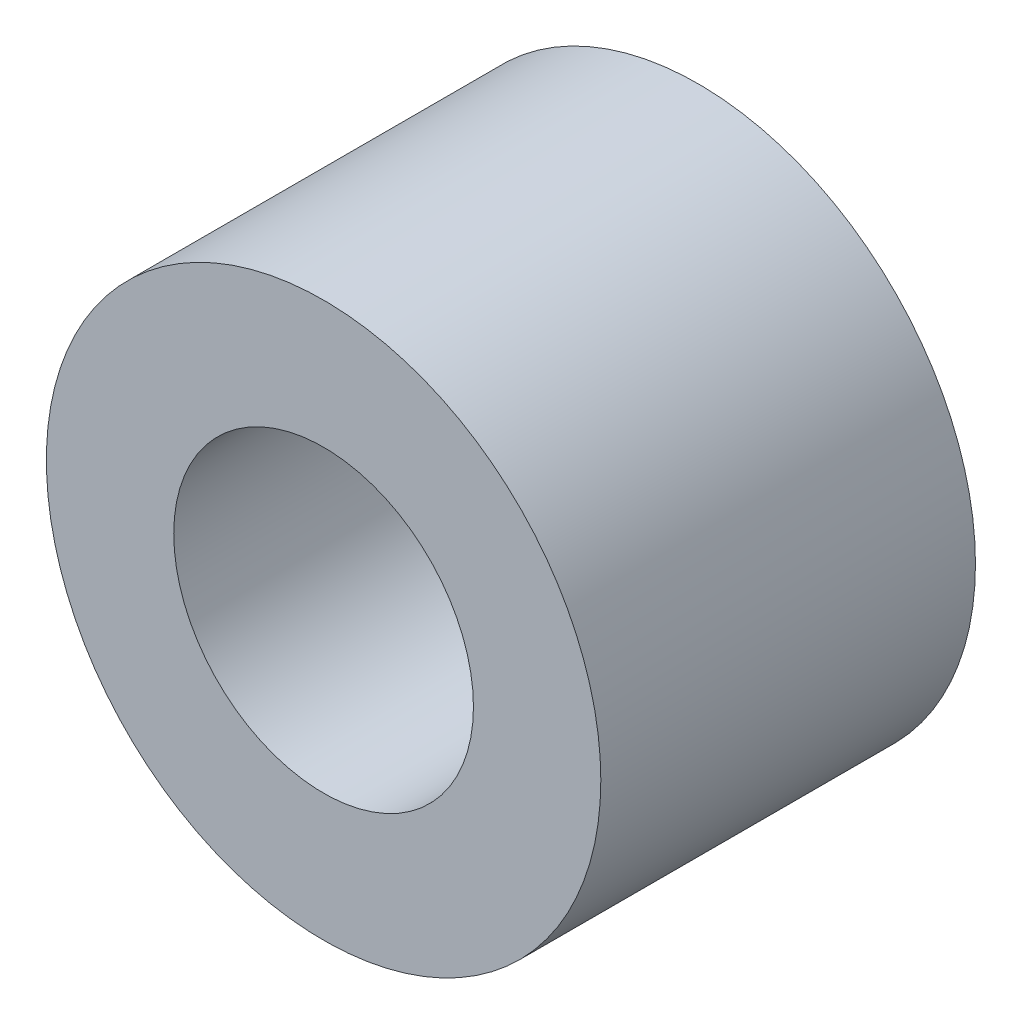
SolidWorks part; units mm, degrees
ref_plane "前视基准面" through (0, 0, 0) normal (0, 0, 1) x (1, 0, 0)
ref_plane "上视基准面" through (0, 0, 0) normal (0, 1, 0) x (1, 0, 0)
ref_plane "右视基准面" through (0, 0, 0) normal (1, 0, 0) x (0, 0, -1)
other "Configuration Table"
sketch "草图1" plane through (0, 0, 0) normal (0, 0, 1) x (1, 0, 0)
  circle A0 centre (0, 0) radius 3.7
extrude "凸台-拉伸1" add sketch "草图1" along normal blind 5
sketch "草图2" plane through (0, 0, 5) normal (0, 0, 1) x (1, 0, 0)
  circle A0 centre (0, 0) radius 2
extrude "切除-拉伸1" cut sketch "草图2" against normal blind 3
sketch "草图3" plane through (0, 0, 2) normal (0, 0, 1) x (1, 0, 0)
  line L1 (1, -1.7321) -> (2, 0)
  line L2 (2, 0) -> (1, 1.7321)
  line L3 (1, 1.7321) -> (-1, 1.7321)
  line L4 (-1, 1.7321) -> (-2, 0)
  line L5 (-2, 0) -> (-1, -1.7321)
  line L6 (-1, -1.7321) -> (1, -1.7321)
  circle A0 centre (0, 0) radius 1.7321 construction
extrude "切除-拉伸2" cut sketch "草图3" against normal blind 4
